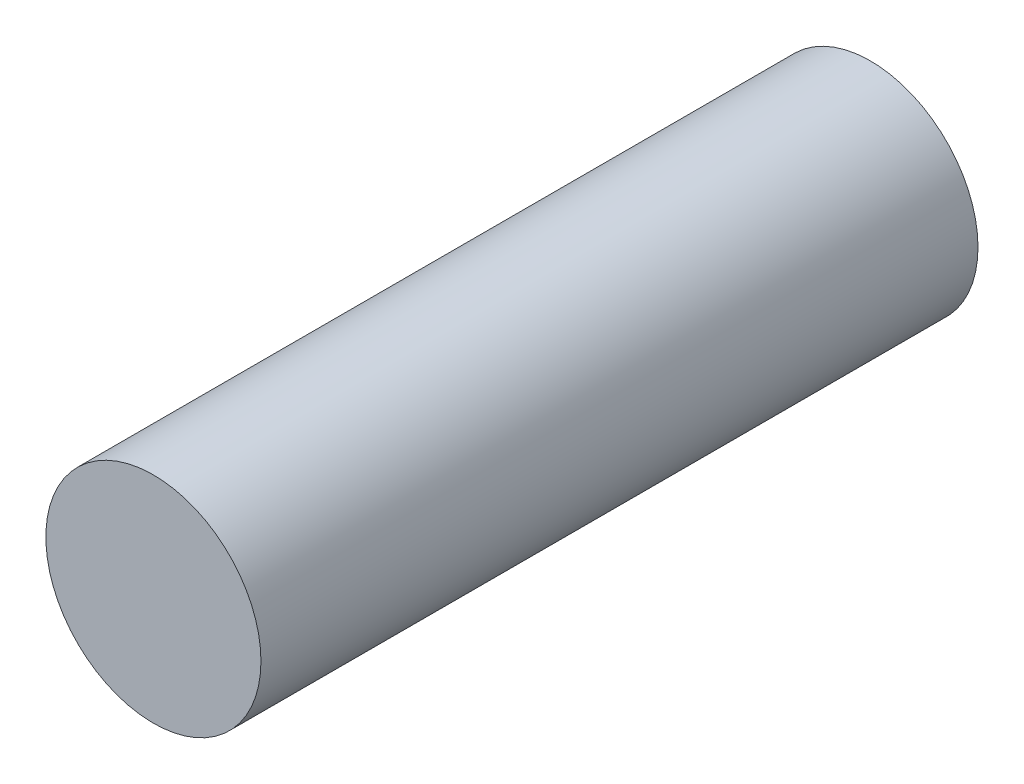
SolidWorks part; units mm, degrees
ref_plane "Front Plane" through (0, 0, 0) normal (0, 0, 1) x (1, 0, 0)
ref_plane "Top Plane" through (0, 0, 0) normal (0, 1, 0) x (1, 0, 0)
ref_plane "Right Plane" through (0, 0, 0) normal (1, 0, 0) x (0, 0, -1)
sketch "Sketch1" plane through (0, 0, 0) normal (0, 0, 1) x (1, 0, 0)
  circle A0 centre (0, 0) radius 76.2
  dimension "D1" = 152.4
extrude "Boss-Extrude1" add sketch "Sketch1" along normal blind 508
